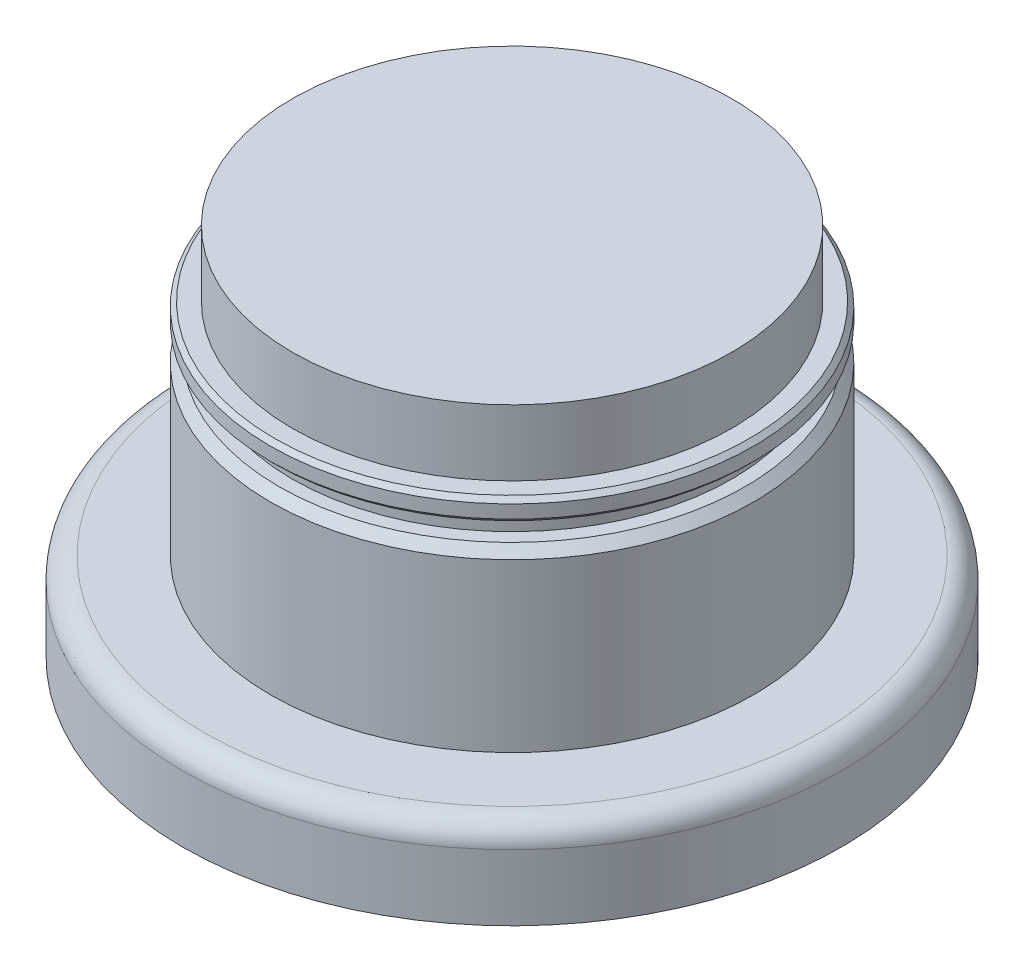
SolidWorks part; units mm, degrees
ref_plane "Front Plane" through (0, 0, 0) normal (0, 0, 1) x (1, 0, 0)
ref_plane "Top Plane" through (0, 0, 0) normal (0, 1, 0) x (1, 0, 0)
ref_plane "Right Plane" through (0, 0, 0) normal (1, 0, 0) x (0, 0, -1)
sketch "Sketch2" plane through (0, 0, 0) normal (0, 1, 0) x (1, 0, 0)
  circle A0 centre (0, 0) radius 75
  dimension "D1" = 150
extrude "Boss-Extrude1" add sketch "Sketch2" along normal blind 20
fillet "Fillet1" radius 5 1 edges at (0, 20, 75)
sketch "Sketch6" plane through (0, 20, 0) normal (0, 1, 0) x (1, 0, 0)
  circle A0 centre (0, 0) radius 55
extrude "Boss-Extrude4" add sketch "Sketch6" along normal blind 40
sketch "Sketch7" plane through (0, 60, 0) normal (0, 1, 0) x (1, 0, 0)
  circle A0 centre (0, 0) radius 50
extrude "Boss-Extrude5" add sketch "Sketch7" along normal blind 5
sketch "Sketch8" plane through (0, 65, 0) normal (0, 1, 0) x (1, 0, 0)
  circle A0 centre (0, 0) radius 55
extrude "Boss-Extrude7" add sketch "Sketch8" along normal blind 5
sketch "Sketch10" plane through (0, 70, 0) normal (0, 1, 0) x (1, 0, 0)
  circle A0 centre (0, 0) radius 50
extrude "Boss-Extrude8" add sketch "Sketch10" along normal blind 15
chamfer "Chamfer7" distance 1 angle 45 2 edges at (0, 65, 55) (0, 70, 55)
chamfer "Chamfer8" distance 2 angle 45 1 edges at (0, 60, 55)
